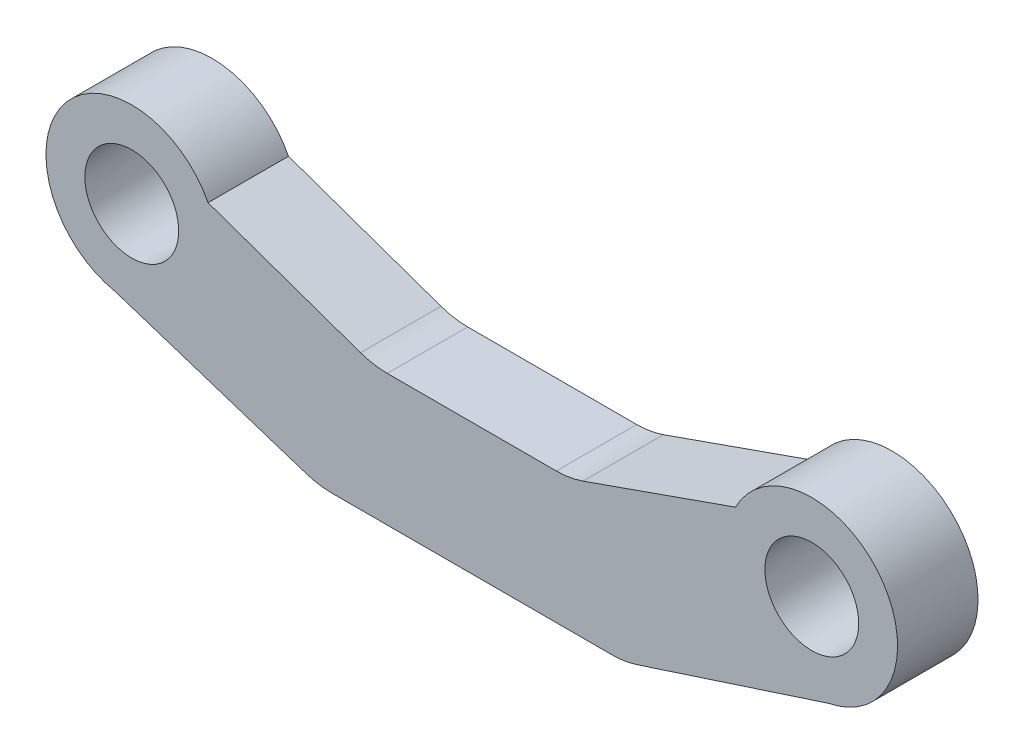
SolidWorks part; units mm, degrees
ref_plane "Alzado" through (0, 0, 0) normal (0, 0, 1) x (1, 0, 0)
ref_plane "Planta" through (0, 0, 0) normal (0, 1, 0) x (1, 0, 0)
ref_plane "Vista lateral" through (0, 0, 0) normal (1, 0, 0) x (0, 0, -1)
sketch "Croquis1" plane through (0, 0, 0) normal (0, 0, 1) x (1, 0, 0)
  line L0 (200, 800) -> (1000, 800) construction
  line L1 (13.8712, 23.2747) -> (24.3301, 23.2747)
  line L2 (25.2578, 23.4218) -> (32.4056, 25.7461)
  line L3 (15.9484, 28.1747) -> (22.2529, 28.1747)
  line L4 (12.9434, 23.4218) -> (5.7956, 25.7461)
  line L5 (14.952, 28.345) -> (9.2656, 30.3471)
  line L6 (23.2493, 28.345) -> (28.9356, 30.3471)
  circle A2 centre (31.7819, 28.8847) radius 1.75
  arc A3 (32.4056, 25.7461) -> (28.9356, 30.3471) centre (31.7819, 28.8847) ccw
  circle A4 centre (6.4194, 28.8847) radius 1.75
  arc A5 (5.7956, 25.7461) -> (9.2656, 30.3471) centre (6.4194, 28.8847) cw
  arc A6 (24.3301, 23.2747) -> (25.2578, 23.4218) centre (24.3301, 26.2747) ccw
  arc A7 (12.9434, 23.4218) -> (13.8712, 23.2747) centre (13.8712, 26.2747) ccw
  arc A8 (22.2529, 28.1747) -> (23.2493, 28.345) centre (22.2529, 31.1747) ccw
  arc A9 (14.952, 28.345) -> (15.9484, 28.1747) centre (15.9484, 31.1747) ccw
  point P16 (19.1006, 23.2747)
  point P17 (19.1006, 28.1747)
  point P18 (19.1006, 23.2747)
  point P19 (19.1006, 28.1747)
  point P20 (19.1006, 28.1747)
  point P23 (24.8056, 23.2747)
  point P26 (13.3956, 23.2747)
  point P29 (22.7656, 28.1747)
  point P32 (15.4356, 28.1747)
  dimension "D2" = 3.5
  dimension "D3" = 6.4
  dimension "D1" = 3
  dimension "D4" = 7.6
  dimension "D5" = 6.17
extrude "Saliente-Extruir1" add sketch "Croquis1" along normal blind 3
